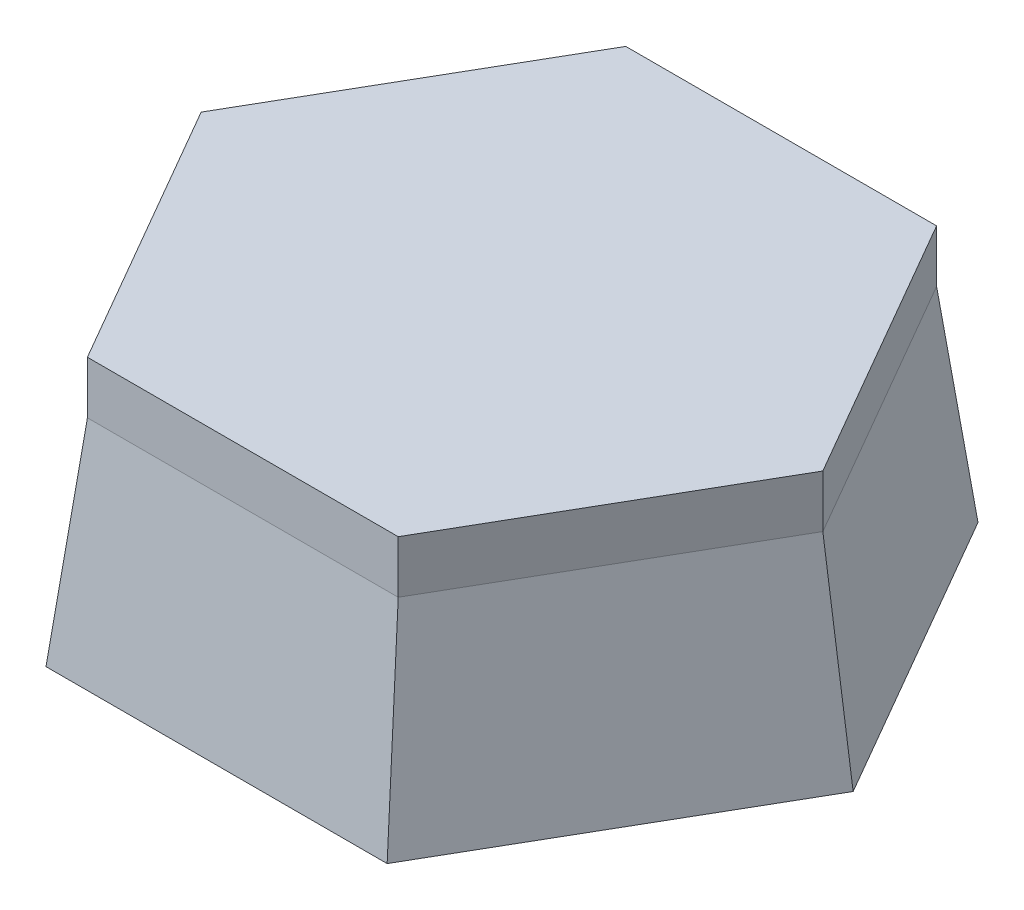
SolidWorks part; units mm, degrees
ref_plane "Front Plane" through (0, 0, 0) normal (0, 0, 1) x (1, 0, 0)
ref_plane "Top Plane" through (0, 0, 0) normal (0, 1, 0) x (1, 0, 0)
ref_plane "Right Plane" through (0, 0, 0) normal (1, 0, 0) x (0, 0, -1)
sketch "Sketch1" plane through (0, 0, 0) normal (0, 1, 0) x (1, 0, 0)
  line L1 (26, 0) -> (13, 22.5167)
  line L2 (13, 22.5167) -> (-13, 22.5167)
  line L3 (-13, 22.5167) -> (-26, 0)
  line L4 (-26, 0) -> (-13, -22.5167)
  line L5 (-13, -22.5167) -> (13, -22.5167)
  line L6 (13, -22.5167) -> (26, 0)
  circle A0 centre (0, 0) radius 22.5167 construction
  dimension "D1" = 52
ref_plane "Plane1" through (0, 16, 0) normal (0, 1, 0) x (1, 0, 0)
sketch "Sketch2" plane through (0, 16, 0) normal (0, 1, 0) x (1, 0, 0)
  line L1 (23.69, 0) -> (11.845, 20.5161)
  line L2 (11.845, 20.5161) -> (-11.845, 20.5161)
  line L3 (-11.845, 20.5161) -> (-23.69, 0)
  line L4 (-23.69, 0) -> (-11.845, -20.5161)
  line L5 (-11.845, -20.5161) -> (11.845, -20.5161)
  line L6 (11.845, -20.5161) -> (23.69, 0)
  circle A0 centre (0, 0) radius 20.5161 construction
  dimension "D1" = 47.38
loft "Loft1" add profiles "Sketch2", "Sketch1"
sketch "Sketch3" plane through (0, 16, 0) normal (0, 1, 0) x (1, 0, 0)
  line L0 (23.69, 0) -> (11.845, 20.5161) construction
  line L1 (11.845, -20.5161) -> (23.69, 0) construction
  line L2 (-11.845, -20.5161) -> (11.845, -20.5161) construction
  line L3 (-23.69, 0) -> (-11.845, -20.5161) construction
  line L4 (-11.845, 20.5161) -> (-23.69, 0) construction
  line L5 (11.845, 20.5161) -> (-11.845, 20.5161) construction
  line L6 (23.69, 0) -> (11.845, 20.5161)
  line L7 (11.845, -20.5161) -> (23.69, 0)
  line L8 (-11.845, -20.5161) -> (11.845, -20.5161)
  line L9 (-23.69, 0) -> (-11.845, -20.5161)
  line L10 (-11.845, 20.5161) -> (-23.69, 0)
  line L11 (11.845, 20.5161) -> (-11.845, 20.5161)
extrude "Boss-Extrude1" add sketch "Sketch3" along normal blind 4
ref_plane "Plane2" through (0, -2, 0) normal (0, -1, 0) x (-1, 0, 0)
sketch "Sketch4" plane through (0, -2, 0) normal (0, -1, 0) x (-1, 0, 0)
  line L1 (23, 0) -> (11.5, 19.9186)
  line L2 (11.5, 19.9186) -> (-11.5, 19.9186)
  line L3 (-11.5, 19.9186) -> (-23, 0)
  line L4 (-23, 0) -> (-11.5, -19.9186)
  line L5 (-11.5, -19.9186) -> (11.5, -19.9186)
  line L6 (11.5, -19.9186) -> (23, 0)
  circle A0 centre (0, 0) radius 19.9186 construction
  dimension "D1" = 46
ref_plane "Plane3" through (0, 16, 0) normal (0, -1, 0) x (-1, 0, 0)
sketch "Sketch5" plane through (0, 16, 0) normal (0, -1, 0) x (-1, 0, 0)
  line L1 (20.69, 0) -> (10.345, 17.9181)
  line L2 (10.345, 17.9181) -> (-10.345, 17.9181)
  line L3 (-10.345, 17.9181) -> (-20.69, 0)
  line L4 (-20.69, 0) -> (-10.345, -17.9181)
  line L5 (-10.345, -17.9181) -> (10.345, -17.9181)
  line L6 (10.345, -17.9181) -> (20.69, 0)
  circle A0 centre (0, 0) radius 17.9181 construction
  dimension "D1" = 41.38
loft "Cut-Loft1" cut profiles "Sketch5", "Sketch4"
